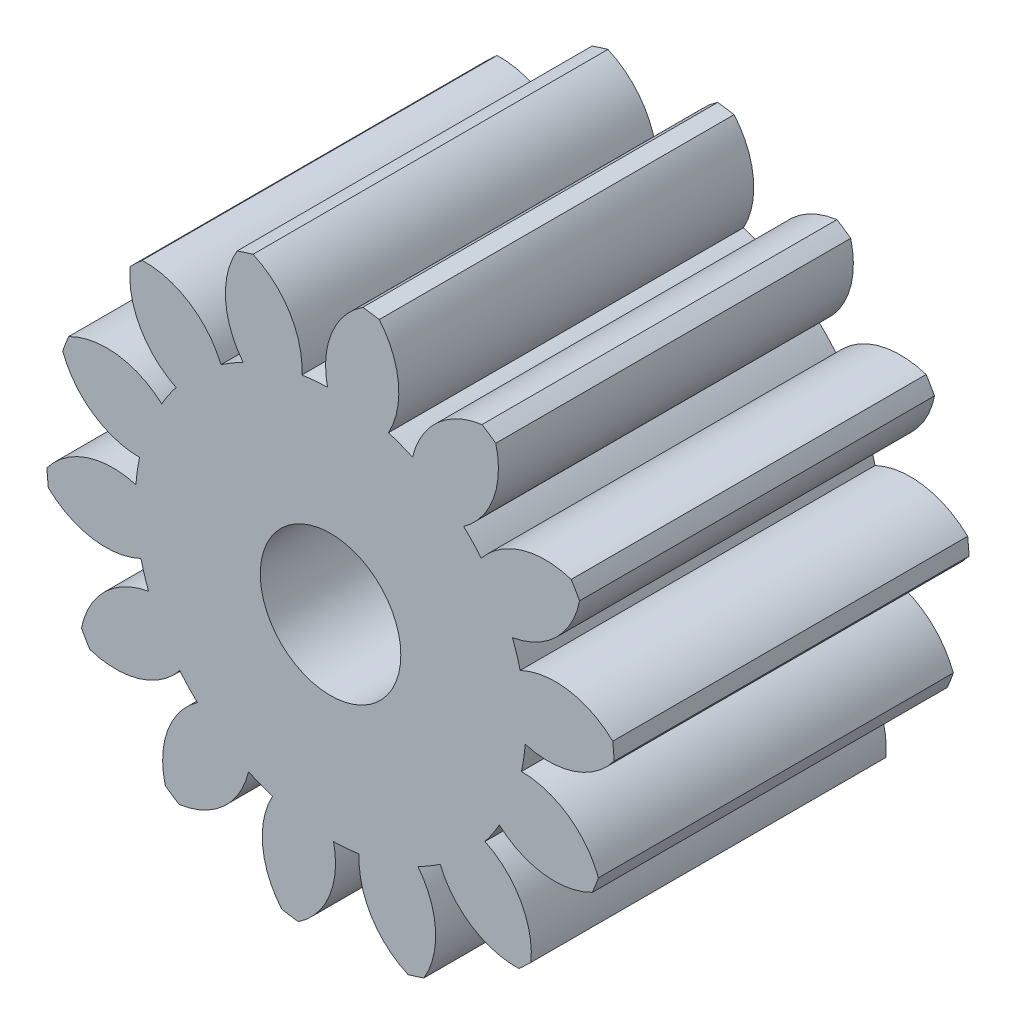
SolidWorks part; units mm, degrees
ref_plane "Alzado" through (0, 0, 0) normal (0, 0, 1) x (1, 0, 0)
ref_plane "Planta" through (0, 0, 0) normal (0, 1, 0) x (1, 0, 0)
ref_plane "Vista lateral" through (0, 0, 0) normal (1, 0, 0) x (0, 0, -1)
sketch "Croquis1" plane through (0, 0, 0) normal (0, 0, 1) x (1, 0, 0)
  circle A0 centre (0, 0) radius 4
  circle A1 centre (0, 0) radius 0.99
  dimension "D1" = 8
  dimension "D2" = 1.98
extrude "Saliente-Extruir1" add sketch "Croquis1" along normal blind 5
sketch "Croquis2" plane through (0, 0, 5) normal (0, 0, 1) x (1, 0, 0)
  line L0 (0, 0) -> (0, 6.1329) construction
  line L1 (0, 0) -> (2.1618, 5.9395) construction
  line L2 (0, 3.4) -> (1.0927, 3.0023) construction
  line L3 (0, 0) -> (-0.5, 6.1329) construction
  circle A0 centre (0, 0) radius 4
  circle A1 centre (0, 0) radius 3.4
  circle A2 centre (0, 0) radius 2.75
  circle A3 centre (1.0927, 3.0023) radius 1.1629
  circle A4 centre (-1.5646, 2.7856) radius 1.1629
  dimension "D1" = 5.5
  dimension "D2" = 6.8
  dimension "D3" = 20
  dimension "D4" = 0.5
extrude "Cortar-Extruir1" cut sketch "Croquis2" against normal blind 5 contours A0 A4 A1 A3 | A1 A4 A2 A3
pattern_circular "MatrizC1" count 14 over 360 about axis through (0, 0, 0) along (0, 0, 1) of "Cortar-Extruir1"
